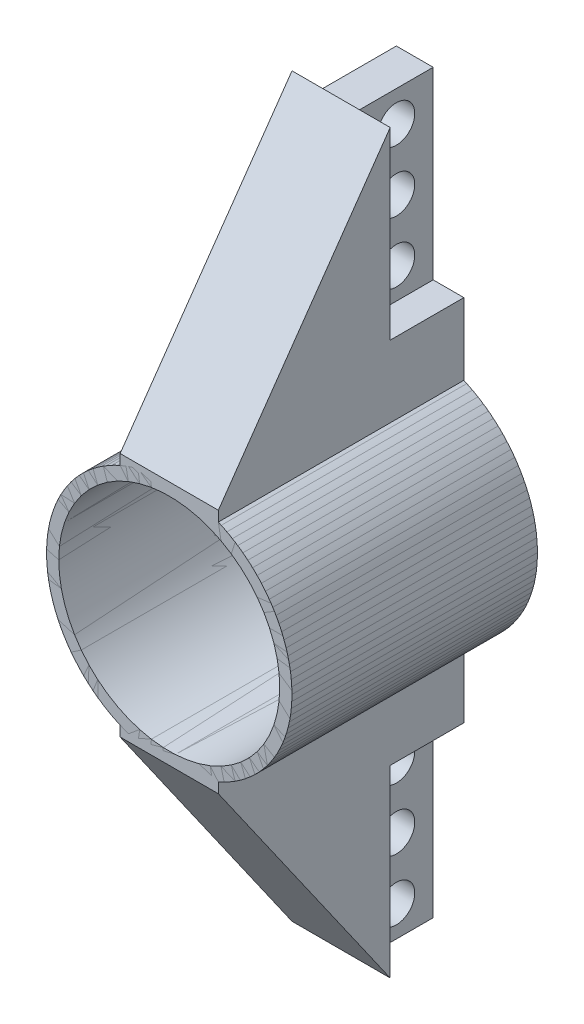
SolidWorks part; units mm, degrees
ref_plane "Front Plane" through (0, 0, 0) normal (0, 0, 1) x (1, 0, 0)
ref_plane "Top Plane" through (0, 0, 0) normal (0, 1, 0) x (1, 0, 0)
ref_plane "Right Plane" through (0, 0, 0) normal (1, 0, 0) x (0, 0, -1)
other "Configuration Table"
sketch "Sketch1" plane through (0, 0, 0) normal (0, 0, 1) x (1, 0, 0)
  circle A0 centre (0, 0) radius 9
  circle A1 centre (0, 0) radius 10
  dimension "D1" = 18
  dimension "D2" = 20
extrude "Boss-Extrude1" add sketch "Sketch1" along normal blind 20
sketch "Sketch2" plane through (0, 0, 0) normal (1, 0, 0) x (0, 0, -1)
  line L0 (-20, 10) -> (-20, 6.5)
  line L2 (-20, 6.5) -> (0, 6.5)
  line L3 (-20, 10) -> (-20, -10) construction
  line L5 (0, 6.5) -> (0, 30)
  line L6 (-20, 10) -> (-6, 30)
  line L7 (-6, 30) -> (0, 30)
  dimension "D1" = 30
  dimension "D2" = 6
  dimension "D3" = 10
extrude "Boss-Extrude2" add sketch "Sketch2" along normal mid plane 8
sketch "Sketch3" plane through (0, 30, 0) normal (0, 1, 0) x (1, 0, 0)
  line L0 (-4, 0) -> (-1.5, 0)
  line L1 (4, 0) -> (-4, 0) construction
  line L2 (-1.5, 0) -> (-1.5, -6)
  line L3 (4, -6) -> (-4, -6) construction
  line L4 (-1.5, -6) -> (-4, -6)
  line L5 (-4, -6) -> (-4, 0)
  line L6 (4, 0) -> (1.5, 0)
  line L7 (1.5, 0) -> (1.5, -6)
  line L8 (1.5, -6) -> (4, -6)
  line L9 (4, -6) -> (4, 0)
  dimension "D1" = 2.5
extrude "Cut-Extrude1" cut sketch "Sketch3" against normal blind 15
sketch "Sketch6" plane through (-1.5, 0, 0) normal (-1, 0, 0) x (0, 0, 1)
  circle A1 centre (3, 17.5) radius 1.5
  circle A2 centre (3, 22.5) radius 1.5
  circle A3 centre (3, 27.5) radius 1.5
  dimension "D4" = 5
  dimension "D5" = 5
move or copy body "Body-Move/Copy1" bodies to move or copy 104 copy yes number of copies 1 rotation origin (0, 0, 0) rotation axis (0, 0, 1) rotation angle 180
sketch "Sketch4" plane through (0, 0, 0) normal (0, 0, -1) x (-1, 0, 0)
  circle A0 centre (0, 0) radius 9
extrude "Cut-Extrude2" cut sketch "Sketch4" against normal through all
extrude "Cut-Extrude3" cut sketch "Sketch6" against normal through all
sketch "Sketch7" plane through (-1.5, 0, 0) normal (-1, 0, 0) x (0, 0, 1)
  circle A1 centre (3, -17.5) radius 1.5
  circle A2 centre (3, -22.5) radius 1.5
  circle A3 centre (3, -27.5) radius 1.5
  dimension "D4" = 5
  dimension "D5" = 5
extrude "Cut-Extrude4" cut sketch "Sketch7" against normal through all
